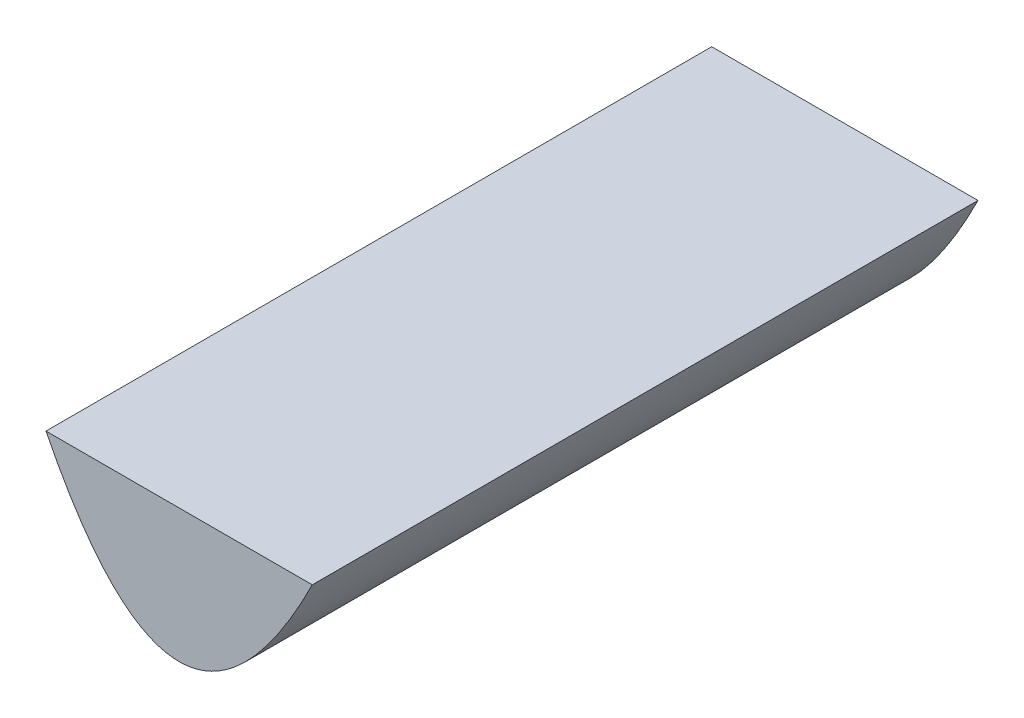
SolidWorks part; units mm, degrees
ref_plane "Front Plane" through (0, 0, 0) normal (0, 0, 1) x (1, 0, 0)
ref_plane "Top Plane" through (0, 0, 0) normal (0, 1, 0) x (1, 0, 0)
ref_plane "Right Plane" through (0, 0, 0) normal (1, 0, 0) x (0, 0, -1)
sketch "Sketch1" plane through (0, 0, 0) normal (0, 0, 1) x (1, 0, 0)
  line L0 (-100, 100) -> (100, 100)
  spline S0 degree 2 poles (-112.6198, 126.8322) (0, -126.8322) (112.6198, 126.8322) knots 0 0 0 1 1 1 construction
  spline S1 degree 2 poles (-100, 100) (0, -100) (100, 100) knots 0.274264 0.274264 0.274264 0.725736 0.725736 0.725736
sketch "Sketch2" plane through (0, 0, 0) normal (1, 0, 0) x (0, 0, -1)
  line L0 (250, 0) -> (-250, 0)
  spline S0 degree 2 poles (-172.7793, 99.9053) (0, -99.9053) (172.7793, 99.9053) knots 0 0 0 1 1 1 construction
  spline S1 degree 2 poles (-149.4048, 74.7024) (0, -74.7024) (149.4048, 74.7024) knots 0.067642 0.067642 0.067642 0.932358 0.932358 0.932358 construction
  point P8 (0, 0)
  dimension "D1" = 500
sweep "Sweep1" add profiles "Sketch1" path "Sketch2"
sketch "Sketch3" plane through (0, 0, 0) normal (1, 0, 0) x (0, 0, -1)
  line L0 (-205.7399, 100) -> (-366.7405, 100)
  line L3 (205.7399, 100) -> (-205.7399, 100)
  line L5 (205.7399, -100) -> (-205.7399, 100) construction
  line L6 (205.7399, 100) -> (-205.7399, -100) construction
  line L7 (-366.7405, 100) -> (-366.7405, 298.5117)
  line L8 (-366.7405, 298.5117) -> (289.4442, 298.5117)
  line L9 (289.4442, 298.5117) -> (289.4442, 100)
  line L10 (289.4442, 100) -> (205.7399, 100)
  point P0 (0, 0)
  dimension "D1" = 100
extrude "Cut-Extrude1" [suppressed] cut sketch "Sketch3" against normal through all both and the other way through all
scale "Scale1" bodies to scale 102 scale about centroid uniform scaling yes scale factor 1.318182
